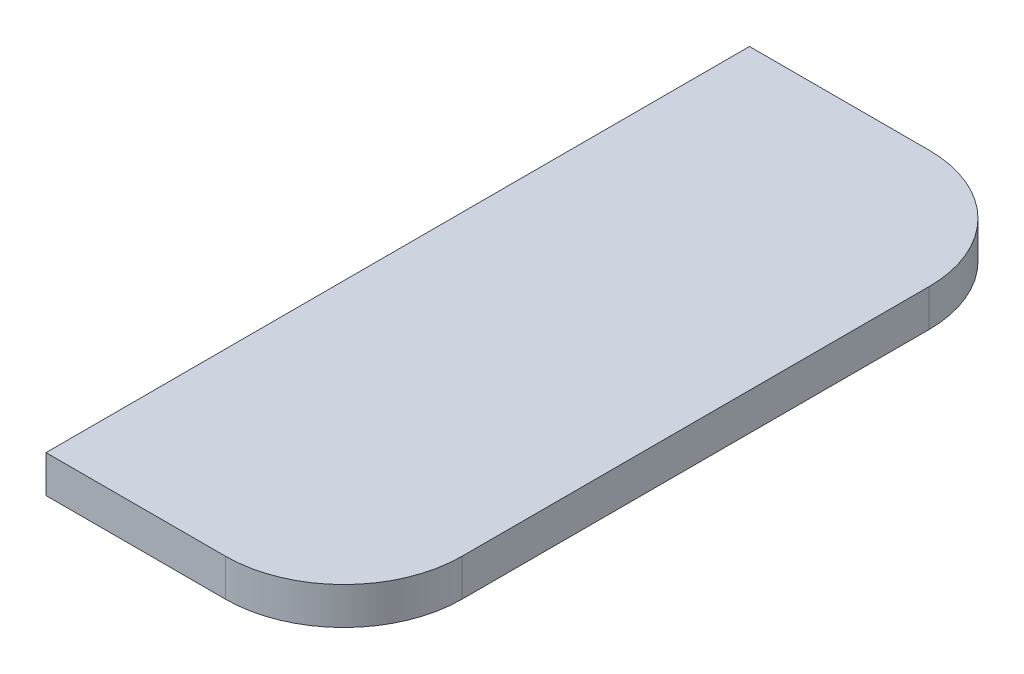
SolidWorks part; units mm, degrees
ref_plane "Front Plane" through (0, 0, 0) normal (0, 0, 1) x (1, 0, 0)
ref_plane "Top Plane" through (0, 0, 0) normal (0, 1, 0) x (1, 0, 0)
ref_plane "Right Plane" through (0, 0, 0) normal (1, 0, 0) x (0, 0, -1)
sketch "Sketch1" plane through (0, 0, 0) normal (0, 1, 0) x (1, 0, 0)
  line L1 (4, -9.45) -> (-4, -9.45)
  line L2 (4, -9.45) -> (4, 9.45)
  line L3 (4, 9.45) -> (-4, 9.45)
  line L4 (-4, -9.45) -> (-4, 9.45)
  line L5 (4, -9.45) -> (-4, 9.45) construction
  line L6 (4, 9.45) -> (-4, -9.45) construction
  point P0 (0, 0)
  dimension "D1" = 18.9
  dimension "D2" = 8
extrude "Boss-Extrude1" add sketch "Sketch1" along normal blind 1
fillet "Fillet1" radius 3.175 2 edges at (4, 0.5, -9.45) (4, 0.5, 9.45)
